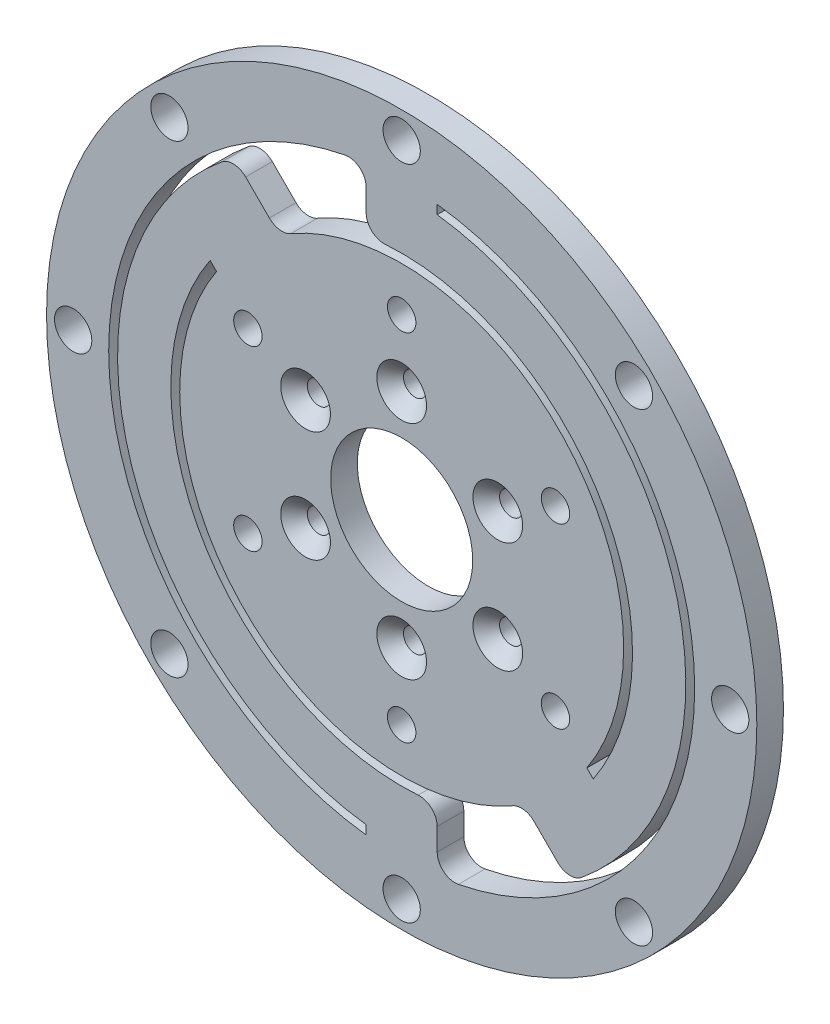
SolidWorks part; units mm, degrees
material "Thornel Mat VMA"
ref_plane "前视基准面" through (0, 0, 0) normal (0, 0, 1) x (1, 0, 0)
ref_plane "上视基准面" through (0, 0, 0) normal (0, 1, 0) x (1, 0, 0)
ref_plane "右视基准面" through (0, 0, 0) normal (1, 0, 0) x (0, 0, -1)
sketch "草图1" plane through (0, 0, 0) normal (0, 0, 1) x (1, 0, 0)
  circle A0 centre (0, 0) radius 40
  circle A1 centre (0, 0) radius 8
  circle A2 centre (0, 0) radius 37 construction
  circle A3 centre (0, 37) radius 2.1
  circle A4 centre (26.163, 26.163) radius 2.1
  circle A5 centre (37, 0) radius 2.1
  circle A6 centre (26.163, -26.163) radius 2.1
  circle A7 centre (0, -37) radius 2.1
  circle A8 centre (-26.163, -26.163) radius 2.1
  circle A9 centre (-37, 0) radius 2.1
  circle A10 centre (-26.163, 26.163) radius 2.1
  circle A11 centre (0, 0) radius 20 construction
  circle A12 centre (0, 20) radius 1.6
  circle A13 centre (17.3205, 10) radius 1.6
  circle A14 centre (17.3205, -10) radius 1.6
  circle A15 centre (0, -20) radius 1.6
  circle A16 centre (-17.3205, -10) radius 1.6
  circle A17 centre (-17.3205, 10) radius 1.6
  circle A18 centre (0, 0) radius 12.5 construction
  circle A19 centre (0, 12.5) radius 1.3
  circle A20 centre (10.8253, 6.25) radius 1.3
  circle A21 centre (10.8253, -6.25) radius 1.3
  circle A22 centre (0, -12.5) radius 1.3
  circle A23 centre (-10.8253, -6.25) radius 1.3
  circle A24 centre (-10.8253, 6.25) radius 1.3
  point P23 (0, 0)
  point P37 (0, 0)
  point P51 (0, 0)
  dimension "D1" = 80
  dimension "D2" = 16
  dimension "D3" = 3
  dimension "D4" = 4.2
  dimension "D6" = 40
  dimension "D7" = 3.2
  dimension "D9" = 25
  dimension "D10" = 2.6
  dimension "D5" = 8
  dimension "D8" = 6
  dimension "D11" = 6
extrude "凸台-拉伸1" add sketch "草图1" along normal blind 3
sketch "草图2" plane through (0, 0, 3) normal (0, 0, 1) x (1, 0, 0)
  line L0 (4, 32.7567) -> (4, 31.749)
  line L5 (-4, 32.7567) -> (-4, 25.6905)
  line L6 (20.856, -13.785) -> (21.5772, -14.5061)
  line L7 (13.785, -20.856) -> (18.814, -25.885)
  line L8 (3.5355, 3.5355) -> (-3.5355, -3.5355) construction
  line L9 (18.7029, -27.1882) -> (12.9184, -21.4036)
  line L10 (-5, 32.619) -> (-5, 24.4949)
  line L11 (-3.5355, -3.5355) -> (13.785, -20.856) construction
  line L12 (3.5355, 3.5355) -> (20.856, -13.785) construction
  arc A2 (18.7029, -27.1882) -> (4, 32.7567) centre (0, 0) ccw
  circle A3 centre (0, 0) radius 40 construction
  arc A4 (18.814, -25.885) -> (4, 31.749) centre (0, 0) ccw
  circle A5 centre (0, 37) radius 2.1 construction
  arc A6 (21.5772, -14.5061) -> (-4, 25.6905) centre (0, 0) ccw
  arc A7 (12.9184, -21.4036) -> (13.785, -20.856) centre (0, 0) ccw
  circle A8 centre (26.163, -26.163) radius 2.1 construction
  arc A9 (-4, 32.7567) -> (-5, 32.619) centre (0, 0) ccw
  arc A10 (20.856, -13.785) -> (-5, 24.4949) centre (0, 0) ccw
  dimension "D1" = 7
  dimension "D2" = 4
  dimension "D3" = 1
  dimension "D4" = 6
  dimension "D5" = 4
  dimension "D7" = 1
  dimension "D6" = 10
  dimension "D8" = 1
  dimension "D9" = 5
  dimension "D10" = 1
extrude "切除-拉伸1" cut sketch "草图2" against normal blind 10
pattern_circular "阵列(圆周)1" count 2 over 360 about axis through (0, 0, 0) along (0, 0, 1) of "切除-拉伸1"
sketch "草图3" plane through (0, 0, 3) normal (0, 0, 1) x (1, 0, 0)
  line L0 (-5, 32.619) -> (-5, 24.4949) construction
  line L1 (-12.9184, 21.4036) -> (-18.7029, 27.1882) construction
  line L2 (-5, 32.619) -> (-5, 24.4949)
  line L3 (-12.9184, 21.4036) -> (-18.7029, 27.1882)
  line L4 (12.9184, -21.4036) -> (18.7029, -27.1882)
  line L5 (5, -32.619) -> (5, -24.4949)
  arc A0 (-5, 32.619) -> (-18.7029, 27.1882) centre (0, 0) ccw
  arc A1 (-5, 24.4949) -> (-12.9184, 21.4036) centre (0, 0) ccw
  arc A2 (5, -32.619) -> (18.7029, -27.1882) centre (0, 0) ccw
  arc A3 (5, -24.4949) -> (12.9184, -21.4036) centre (0, 0) ccw
  point P15 (0, 0)
  dimension "D1" = 2
extrude "切除-拉伸2" cut sketch "草图3" against normal blind 10
fillet "圆角1" radius 2 8 edges at (-4, 32.7567, 1.5) (-4, 25.6905, 1.5) (13.785, -20.856, 1.5) (18.814, -25.885, 1.5) (4, -32.7567, 1.5) (4, -25.6905, 1.5) (-13.785, 20.856, 1.5) (-18.814, 25.885, 1.5)
chamfer "倒角1" distance 1.5 angle 45 6 edges at (-9.5253, -6.25, 3) (1.3, -12.5, 3) (12.1253, -6.25, 3) (12.1253, 6.25, 3) (1.3, 12.5, 3) (-9.5253, 6.25, 3)
